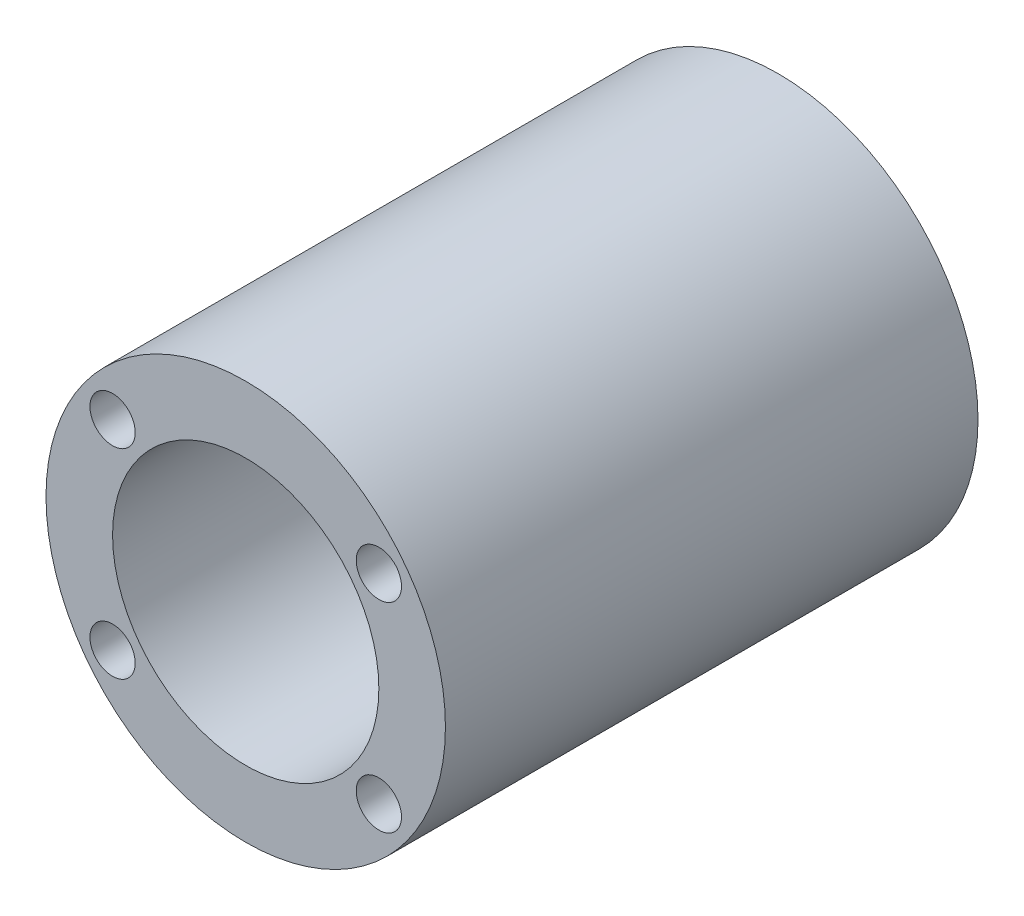
SolidWorks part; units mm, degrees
ref_plane "Front Plane" through (0, 0, 0) normal (0, 0, 1) x (1, 0, 0)
ref_plane "Top Plane" through (0, 0, 0) normal (0, 1, 0) x (1, 0, 0)
ref_plane "Right Plane" through (0, 0, 0) normal (1, 0, 0) x (0, 0, -1)
sketch "Sketch1" plane through (0, 0, 0) normal (0, 0, 1) x (1, 0, 0)
  circle A0 centre (0, 0) radius 30
  circle A1 centre (0, 0) radius 20
  point P16 (0, 0)
  dimension "D1" = 60
  dimension "D2" = 10
extrude "Boss-Extrude1" add sketch "Sketch1" along normal mid plane 80
sketch "Sketch2" plane through (0, 0, 40) normal (0, 0, 1) x (1, 0, 0)
  line L0 (20, 0) -> (30, 0) construction
  line L1 (0, 14.5015) -> (0, -10.9957) construction
  circle A0 centre (0, 0) radius 20 construction
  circle A1 centre (0, 0) radius 30 construction
  circle A2 centre (0, 0) radius 25 construction
  point P6 (25, 0)
  point P7 (-20, 15)
  point P11 (-20, -15)
  point P14 (20, -15)
  point P15 (20, 15)
  dimension "D2" = 40
  dimension "D1" = 30
hole_wizard "Tap Drill for M8x1.25 Tap1" positions "3DSketch1" profile "Sketch12" hole size "M8x1.25" standard "ANSI Metric"
sketch3d "3DSketch1"
  point P0 (-20, 15, 40)
  point P3 (20, 15, 40)
  point P6 (20, -15, 40)
  point P9 (-20, -15, 40)
sketch "Sketch12" plane through (-20, 15, 40) normal (1, 0, 0) x (0, -1, 0)
  line L0 (0, 0) -> (0, 22.0429)
  line L1 (0, 22.0429) -> (3.4, 20)
  line L2 (3.4, 20) -> (3.4, 0)
  line L5 (3.4, 0) -> (0, 0)
  line L10 (0, 22.0429) -> (-3.4, 20) construction
  line L11 (0, -6.35) -> (0, 107.95) construction
  dimension "Hole Dia." = 6.8
  dimension "Hole Depth" = 20
  dimension "Drill Angle" = 118
mirror "Mirror1" about plane through (0, 0, 0) normal (0, 0, 1) of "Tap Drill for M8x1.25 Tap1"
